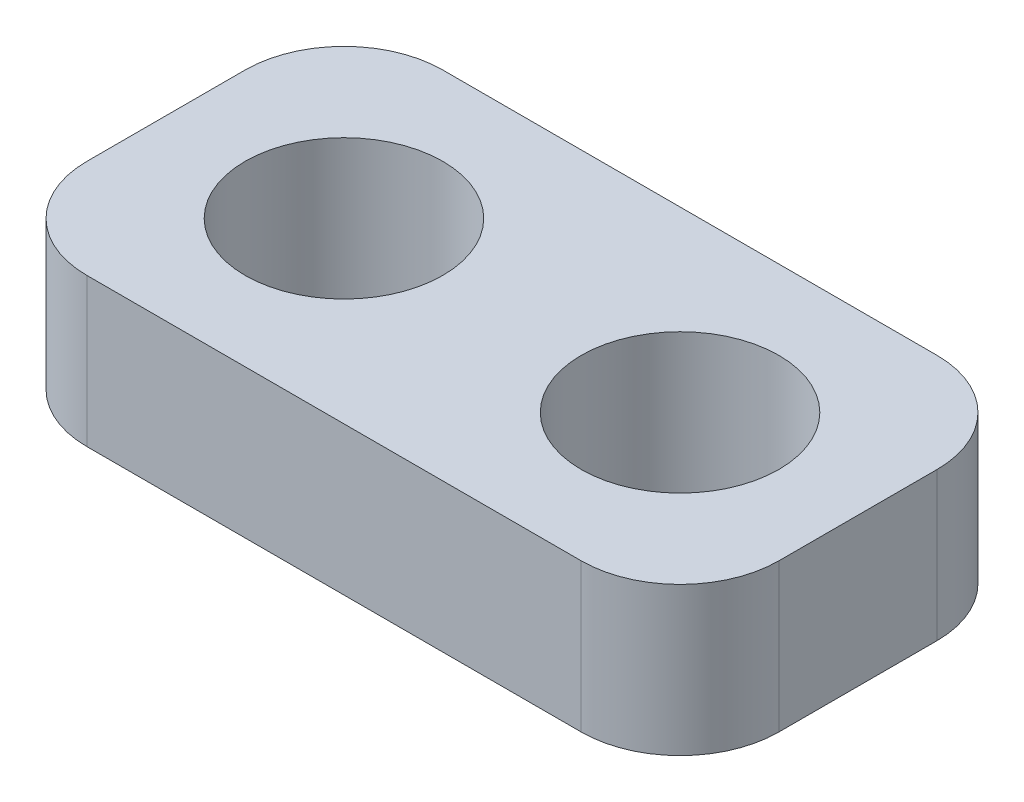
SolidWorks part; units mm, degrees
ref_plane "Front Plane" through (0, 0, 0) normal (0, 0, 1) x (1, 0, 0)
ref_plane "Top Plane" through (0, 0, 0) normal (0, 1, 0) x (1, 0, 0)
ref_plane "Right Plane" through (0, 0, 0) normal (1, 0, 0) x (0, 0, -1)
sketch "Sketch1" plane through (0, 0, 0) normal (0, 1, 0) x (1, 0, 0)
  line L0 (-52, 18) -> (-52, -18)
  line L1 (-52, -18) -> (18, -18)
  line L2 (18, -18) -> (18, 18)
  line L3 (18, 18) -> (-52, 18)
  line L4 (-55, 0) -> (55, 0) construction
  circle A0 centre (0, 0) radius 10
  circle A1 centre (-34, 0) radius 10
  point P5 (-34, 0)
  point P10 (-65.5836, 24.6758)
  point P15 (31.3891, -1.8682)
  dimension "D1" = 34
  dimension "D2" = 20
  dimension "D3" = 20
  dimension "D4" = 18
  dimension "D5" = 18
  dimension "D6" = 18
  dimension "D7" = 18
extrude "Boss-Extrude1" add sketch "Sketch1" along normal blind 15
fillet "Fillet1" radius 10 4 edges at (-52, 7.5, -18) (18, 7.5, -18) (18, 7.5, 18) (-52, 7.5, 18)
